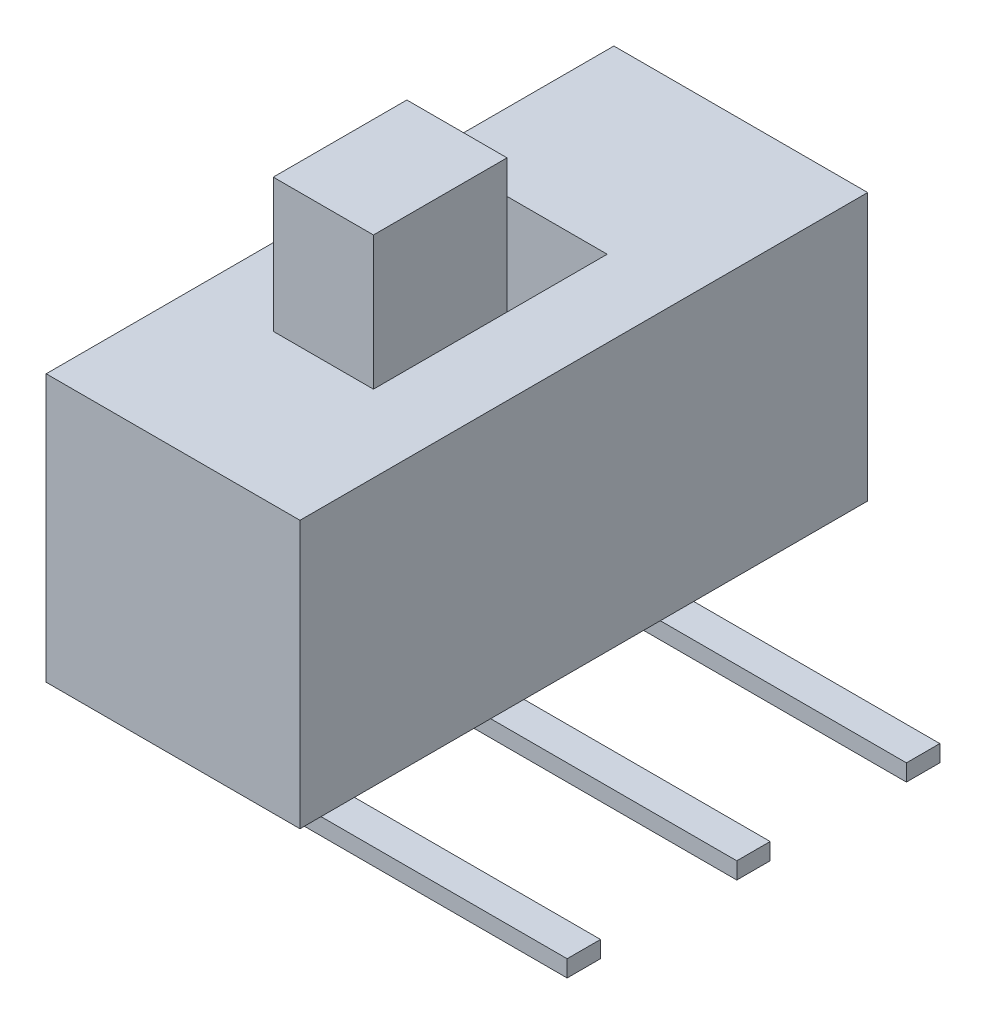
SolidWorks part; units mm, degrees
ref_plane "前视" through (0, 0, 0) normal (0, 0, 1) x (1, 0, 0)
ref_plane "上视" through (0, 0, 0) normal (0, 1, 0) x (1, 0, 0)
ref_plane "右视" through (0, 0, 0) normal (1, 0, 0) x (0, 0, -1)
sketch "草图1" plane through (0, 0, 0) normal (0, 1, 0) x (1, 0, 0)
  line L0 (0, 84.5395) -> (0, -95.7315) construction
  line L1 (-112.9192, 0) -> (128.508, 0) construction
  line L3 (-1.9, 4.25) -> (1.9, 4.25)
  line L4 (-1.9, 4.25) -> (-1.9, -4.25)
  line L5 (-1.9, -4.25) -> (1.9, -4.25)
  line L6 (1.9, 4.25) -> (1.9, -4.25)
  dimension "D1" = 3.8
  dimension "D2" = 8.5
extrude "拉伸1" add sketch "草图1" along normal blind 4
sketch "草图2" plane through (0, 4, 0) normal (0, 1, 0) x (-1, 0, 0)
  line L0 (0, -9.1531) -> (0, 9.348) construction
  line L1 (-6.307, 0) -> (6.9767, 0) construction
  line L2 (1.9, -4.25) -> (1.9, 4.25) construction
  line L3 (-0.8, -2) -> (1, -2) construction
  line L4 (-0.8, -2) -> (-0.8, 2) construction
  line L5 (-0.8, 2) -> (1, 2) construction
  line L6 (1, -2) -> (1, 2) construction
  line L7 (-0.75, 0) -> (0.75, 0)
  line L8 (-0.75, 0) -> (-0.75, 2)
  line L9 (-0.75, 2) -> (0.75, 2)
  line L10 (0.75, 0) -> (0.75, 2)
  dimension "D1" = 4
  dimension "D2" = 1.8
  dimension "D3" = 1.5
  dimension "D4" = 2
  dimension "D5" = 0.9
extrude "拉伸2" add sketch "草图2" along normal blind 2
sketch "草图5" plane through (0, 4, 0) normal (0, 1, 0) x (-1, 0, 0)
  line L0 (0, -8.8679) -> (0, 9.7834) construction
  line L1 (-0.75, -1.5) -> (0.75, -1.5)
  line L2 (-0.75, -1.5) -> (-0.75, 2)
  line L3 (-0.75, 2) -> (0.75, 2)
  line L4 (0.75, -1.5) -> (0.75, 2)
  line L5 (0.75, 2) -> (-0.75, 2) construction
  dimension "D1" = 1.5
  dimension "D2" = 3.5
extrude "切除-拉伸1" cut sketch "草图5" against normal blind 2
sketch "草图6" plane through (-1.9, 0, 0) normal (-1, 0, 0) x (0, 0, 1)
  line L0 (0, 0) -> (0, 19.3638)
sketch "草图7" plane through (0, 0, 0) normal (0, -1, 0) x (1, 0, 0)
  line L0 (0, 6.1791) -> (0, -6.618) construction
  line L1 (-5.0311, 0) -> (4.6259, 0) construction
  line L2 (-0.125, 2.79) -> (-0.125, 2.29)
  line L3 (-0.125, 0.25) -> (0.125, 0.25)
  line L4 (-0.125, 0.25) -> (-0.125, -0.25)
  line L5 (-0.125, -0.25) -> (0.125, -0.25)
  line L6 (0.125, 0.25) -> (0.125, -0.25)
  line L7 (0.125, 2.79) -> (0.125, 2.29)
  line L8 (-0.125, 2.79) -> (0.125, 2.79)
  line L9 (-0.125, 2.29) -> (0.125, 2.29)
  line L10 (3.0558, 2.54) -> (-2.9072, 2.54) construction
  line L11 (-0.125, -2.29) -> (0.125, -2.29)
  line L12 (-0.125, -2.79) -> (0.125, -2.79)
  line L13 (0.125, -2.79) -> (0.125, -2.29)
  line L14 (-0.125, -2.79) -> (-0.125, -2.29)
  dimension "D1" = 0.25
  dimension "D2" = 0.5
  dimension "D3" = 0.25
  dimension "D4" = 0.5
  dimension "D5" = 2.54
sketch "草图9" plane through (0, 0, 4.25) normal (0, 0, 1) x (1, 0, 0)
  line L0 (0, 0) -> (0, -1.27)
  line L1 (0, -1.27) -> (4.44, -1.27)
  line L2 (3.0558, 0) -> (-2.9072, 0) construction
  line L3 (1.9, 4) -> (1.9, 0) construction
  dimension "D1" = 1.27
  dimension "D2" = 2.54
sweep "扫描1" add profiles "草图7" path "草图9"
ref_plane "基准面1" through (0, 0, 1) normal (0, 0, 1) x (1, 0, 0)
